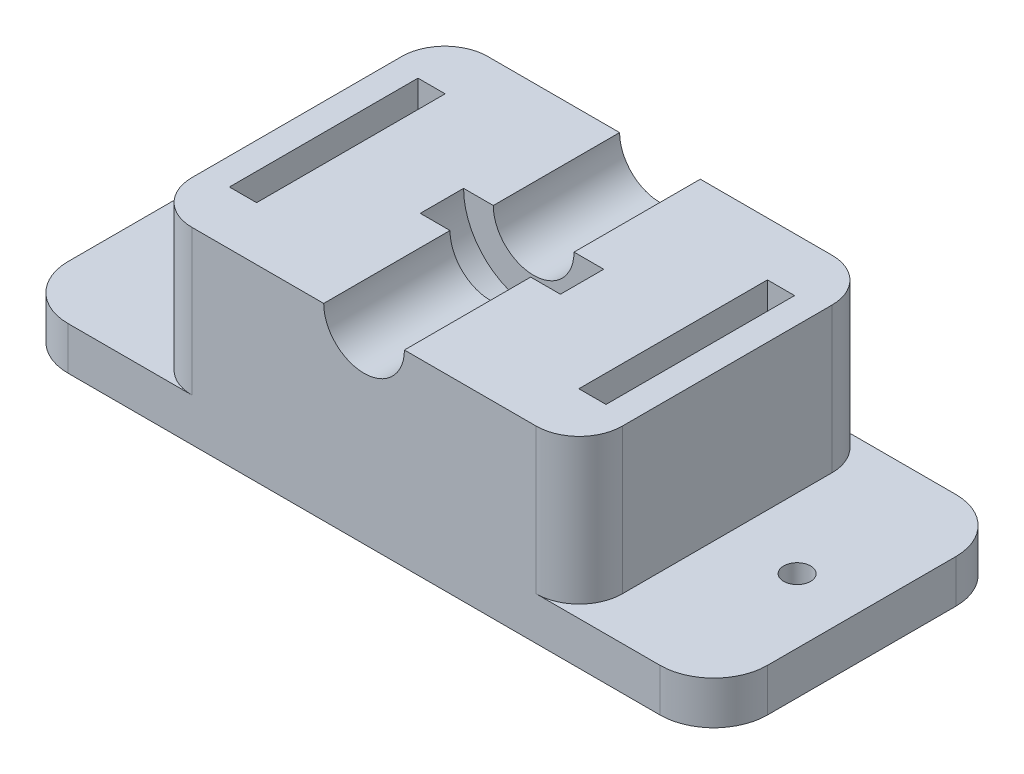
SolidWorks part; units mm, degrees
ref_plane "Alzado" through (0, 0, 0) normal (0, 0, 1) x (1, 0, 0)
ref_plane "Planta" through (0, 0, 0) normal (0, 1, 0) x (1, 0, 0)
ref_plane "Vista lateral" through (0, 0, 0) normal (1, 0, 0) x (0, 0, -1)
sketch "Croquis1" plane through (0, 0, 0) normal (0, 0, 1) x (1, 0, 0)
  line L0 (-40, 0) -> (40, 0)
  line L1 (40, 0) -> (40, -27)
  line L2 (40, -35) -> (-40, -35)
  line L3 (-40, -27) -> (-40, 0)
  line L5 (-40, -35) -> (-65, -35)
  line L7 (-40, -27) -> (-65, -27)
  line L8 (-65, -35) -> (-65, -27)
  line L9 (40, -35) -> (65, -35)
  line L11 (40, -27) -> (65, -27)
  line L12 (65, -35) -> (65, -27)
  dimension "D1" = 80
  dimension "D4" = 25
  dimension "D2" = 35
  dimension "D3" = 25
  dimension "D5" = 8
  dimension "D6" = 8
extrude "Saliente-Extruir1" add sketch "Croquis1" along normal blind 55
ref_plane "Plano1" through (0, 0, 27.5) normal (0, 0, 1) x (1, 0, 0)
sketch "Croquis2" plane through (0, 0, 27.5) normal (0, 0, 1) x (1, 0, 0)
  circle A0 centre (0, 0) radius 13.025
  dimension "D1" = 26.05
extrude "Cortar-Extruir1" cut sketch "Croquis2" against normal mid plane 8.05
sketch "Croquis3" plane through (0, 0, 0) normal (0, 1, 0) x (1, 0, 0)
  line L0 (40, 0) -> (-40, 0) construction
  line L1 (-35, -9.975) -> (-29.95, -9.975)
  line L2 (-35, -9.975) -> (-35, -45.025)
  line L3 (-35, -45.025) -> (-29.95, -45.025)
  line L4 (-29.95, -9.975) -> (-29.95, -45.025)
  line L10 (-40, -55) -> (-40, 0) construction
  line L11 (0, 20.6246) -> (0, -67.1314) construction
  line L12 (35, -45.025) -> (29.95, -45.025)
  line L13 (29.95, -9.975) -> (29.95, -45.025)
  line L14 (35, -9.975) -> (29.95, -9.975)
  line L15 (35, -9.975) -> (35, -45.025)
  point P10 (-29.95, -27.5)
  dimension "D1" = 35.05
  dimension "D2" = 27.5
  dimension "D3" = 5.05
  dimension "D7" = 5
extrude "Cortar-Extruir2" cut sketch "Croquis3" against normal blind 10
sketch "Croquis4" plane through (0, 0, 27.5) normal (0, 0, 1) x (1, 0, 0)
  circle A0 centre (0, 0) radius 7.5
  dimension "D1" = 15
extrude "Cortar-Extruir3" cut sketch "Croquis4" against normal through all both and the other way through all
fillet "Redondeo1" radius 10 4 edges at (65, -31, 0) (65, -31, 55) (-65, -31, 0) (-65, -31, 55)
sketch "Croquis5" plane through (0, -27, 0) normal (0, 1, 0) x (1, 0, 0)
  line L0 (0, 11.3752) -> (0, -14.9619) construction
  line L2 (-40, -55) -> (-55, -55) construction
  circle A0 centre (-53, -27.5) radius 2.5
  circle A2 centre (53, -27.5) radius 2.5
  dimension "D1" = 5
  dimension "D2" = 53
  dimension "D3" = 27.5
extrude "Cortar-Extruir4" cut sketch "Croquis5" against normal through all
fillet "Redondeo2" radius 8 4 edges at (-40, -13.5, 0) (40, -13.5, 0) (40, -13.5, 55) (-40, -13.5, 55)
